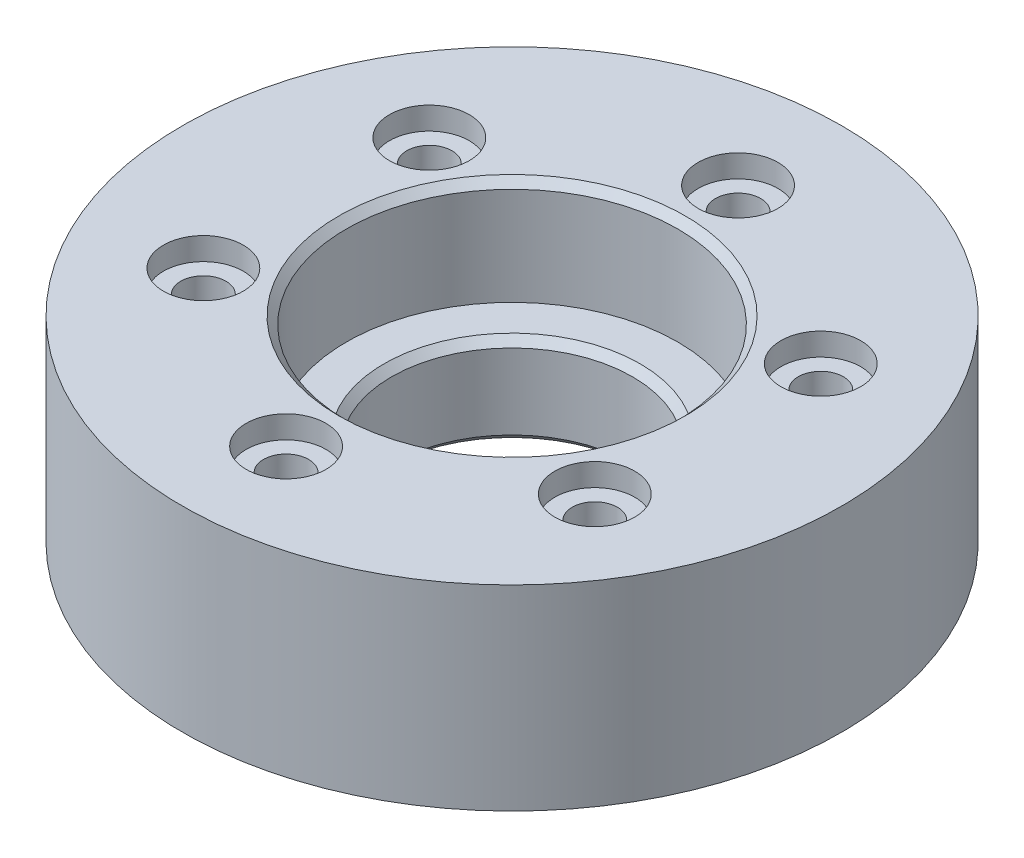
SolidWorks part; units mm, degrees
ref_plane "Front" through (0, 0, 0) normal (0, 0, 1) x (1, 0, 0)
ref_plane "Top" through (0, 0, 0) normal (0, 1, 0) x (1, 0, 0)
ref_plane "Right" through (0, 0, 0) normal (1, 0, 0) x (0, 0, -1)
sketch "Sketch1" plane through (0, 0, 0) normal (0, 1, 0) x (1, 0, 0)
  circle A0 centre (0, 0) radius 21.875
  dimension "D1" = 43.75
extrude "Boss-Extrude1" add sketch "Sketch1" along normal blind 13
sketch "Sketch2" plane through (0, 13, 0) normal (0, 1, 0) x (1, 0, 0)
  circle A0 centre (0, 0) radius 11
  dimension "D1" = 22
extrude "Cut-Extrude1" cut sketch "Sketch2" against normal blind 7
sketch "Sketch3" plane through (0, 6, 0) normal (0, 1, 0) x (1, 0, 0)
  circle A0 centre (0, 0) radius 8
  dimension "D1" = 16
extrude "Cut-Extrude2" cut sketch "Sketch3" against normal up to next
sketch "Sketch4" plane through (0, 13, 0) normal (0, 1, 0) x (1, 0, 0)
  circle A0 centre (0, 15) radius 1.5
  dimension "D1" = 3
  dimension "D2" = 15
extrude "Cut-Extrude3" cut sketch "Sketch4" against normal up to next
pattern_circular "CirPattern1" count 6 over 360 about axis through (0, 0, 0) along (0, 1, 0) of "Cut-Extrude3"
chamfer "Chamfer1" distance 0.5 angle 45 3 edges at (0, 0, 8) (0, 6, 8) (0, 13, 11)
sketch "Sketch5" plane through (0, 13, 0) normal (0, 1, 0) x (1, 0, 0)
  circle A0 centre (0, 15) radius 2.65
  dimension "D1" = 5.3
extrude "Cut-Extrude4" cut sketch "Sketch5" against normal blind 1.5
pattern_circular "CirPattern2" count 6 over 360 about axis through (0, 0, 0) along (0, 1, 0) of "Cut-Extrude4"
sketch "Sketch6" plane through (0, 0, 0) normal (0, -1, 0) x (-1, 0, 0)
  line L0 (0, 0) -> (12.9904, 7.5) construction
  line L1 (14.6358, 10.35) -> (11.3449, 10.35)
  line L2 (11.3449, 10.35) -> (9.6995, 7.5)
  line L3 (9.6995, 7.5) -> (11.3449, 4.65)
  line L4 (11.3449, 4.65) -> (14.6358, 4.65)
  line L5 (14.6358, 4.65) -> (16.2813, 7.5)
  line L6 (16.2813, 7.5) -> (14.6358, 10.35)
  line L7 (0, 0) -> (0, 15) construction
  line L8 (3.2909, 15) -> (1.6454, 17.85)
  line L9 (1.6454, 17.85) -> (-1.6454, 17.85)
  line L10 (-1.6454, 17.85) -> (-3.2909, 15)
  line L11 (-3.2909, 15) -> (-1.6454, 12.15)
  line L12 (-1.6454, 12.15) -> (1.6454, 12.15)
  line L13 (1.6454, 12.15) -> (3.2909, 15)
  line L14 (-11.3449, 10.35) -> (-14.6358, 10.35)
  line L15 (-14.6358, 10.35) -> (-16.2813, 7.5)
  line L16 (-16.2813, 7.5) -> (-14.6358, 4.65)
  line L17 (-14.6358, 4.65) -> (-11.3449, 4.65)
  line L18 (-11.3449, 4.65) -> (-9.6995, 7.5)
  line L19 (-9.6995, 7.5) -> (-11.3449, 10.35)
  line L20 (0, 0) -> (-12.9904, 7.5) construction
  circle A0 centre (12.9904, 7.5) radius 2.85 construction
  circle A1 centre (0, 15) radius 2.85 construction
  circle A2 centre (-12.9904, 7.5) radius 2.85 construction
  dimension "D1" = 5.7
  dimension "D2" = 5.7
  dimension "D3" = 5.7
extrude "Cut-Extrude5" cut sketch "Sketch6" against normal blind 1.5
mirror "Mirror1" about plane through (0, 0, 0) normal (0, 0, 1) of "Cut-Extrude5"
